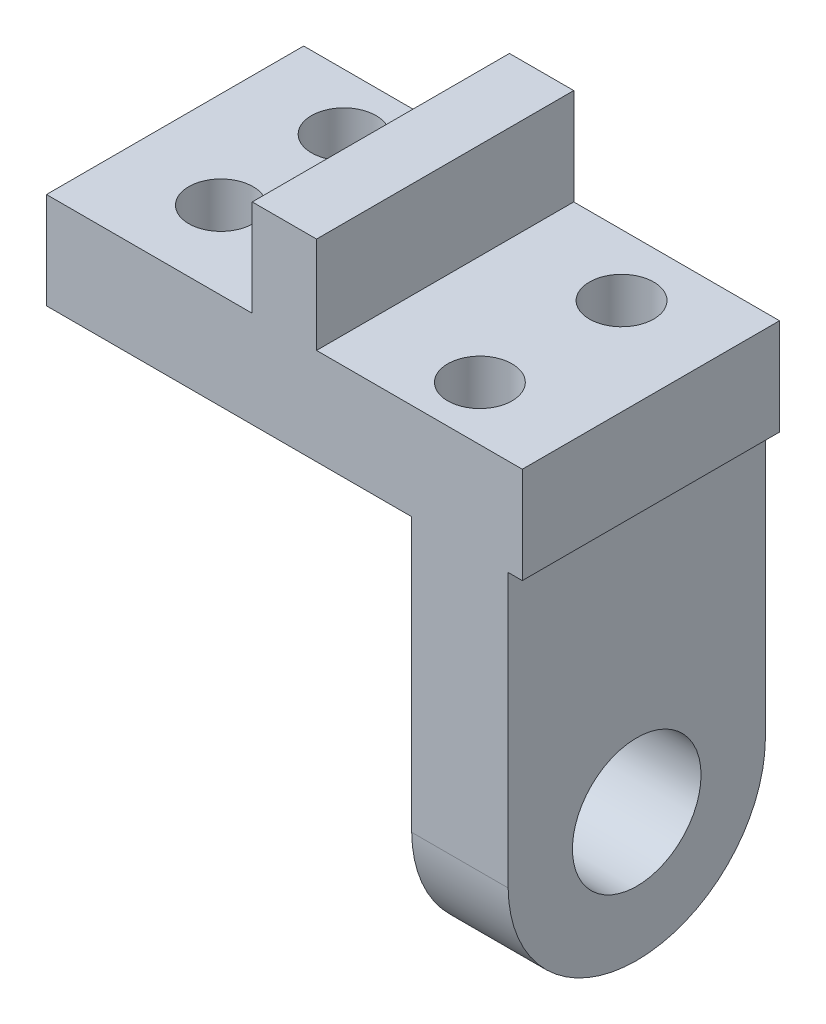
SolidWorks part; units mm, degrees
ref_plane "Front Plane" through (0, 0, 0) normal (0, 0, 1) x (1, 0, 0)
ref_plane "Top Plane" through (0, 0, 0) normal (0, 1, 0) x (1, 0, 0)
ref_plane "Right Plane" through (0, 0, 0) normal (1, 0, 0) x (0, 0, -1)
sketch "Sketch1" plane through (0, 0, 0) normal (0, 0, 1) x (1, 0, 0)
  line L1 (-56.7949, 15) -> (17.2051, 15)
  line L2 (-56.7949, 15) -> (-56.7949, 0)
  line L3 (-56.7949, 0) -> (17.2051, 0)
  line L4 (17.2051, 15) -> (17.2051, 0)
  dimension "D1" = 15
  dimension "D2" = 74
extrude "Boss-Extrude1" add sketch "Sketch1" along normal mid plane 40
sketch "Sketch2" plane through (0, 0, 0) normal (0, 1, 0) x (1, 0, 0)
  line L0 (-19.7949, 20) -> (-19.7949, -20) construction
  line L1 (17.2051, 20) -> (-56.7949, 20) construction
  line L2 (17.2051, -20) -> (-56.7949, -20) construction
  line L6 (-25.0987, -20) -> (-14.5497, -20)
  line L8 (-24.7949, 20) -> (-14.7949, 20)
  line L9 (-24.7949, 20) -> (-24.7949, -20)
  line L10 (-24.7949, -20) -> (-14.7949, -20)
  line L11 (-14.7949, 20) -> (-14.7949, -20)
  dimension "D1" = 10
  dimension "D2" = 5
extrude "Boss-Extrude2" add sketch "Sketch2" along normal blind 30 contours L9 L10 L11 L8
sketch "Sketch3" plane through (0, 0, 0) normal (0, 1, 0) x (1, 0, 0)
  line L0 (-56.7949, -20) -> (-56.7949, 20) construction
  circle A0 centre (-41.7949, 11.2385) radius 5.0247
  circle A1 centre (-41.7949, -5.5592) radius 5.0139
  point P6 (0, 0)
  point P7 (0, 0)
  dimension "D1" = 15
  dimension "D2" = 15
extrude "Cut-Extrude4" cut sketch "Sketch3" along normal up to surface (15 mm away) contours A0 up to face at (-40.7949, 15, 0)
sketch "Sketch6" plane through (0, 15, 0) normal (0, 1, 0) x (1, 0, 0)
  circle A0 centre (-41.7949, -7.8749) radius 5
extrude "Cut-Extrude5" cut sketch "Sketch6" against normal blind 30
sketch "Sketch8" plane through (0, 15, 0) normal (0, 1, 0) x (1, 0, 0)
  line L0 (17.2051, -20) -> (17.2051, 20) construction
  circle A0 centre (2.2051, 10.4357) radius 5
  dimension "D1" = 15
extrude "Cut-Extrude6" cut sketch "Sketch8" against normal blind 30
sketch "Sketch9" plane through (0, 15, 0) normal (0, 1, 0) x (1, 0, 0)
  line L0 (17.2051, -20) -> (17.2051, 20) construction
  circle A0 centre (2.2051, -11.5981) radius 5
  dimension "D1" = 15
extrude "Cut-Extrude7" cut sketch "Sketch9" against normal blind 30
sketch "Sketch11" plane through (0, 0, 0) normal (1, 0, 0) x (0, 0, -1)
  line L0 (-20, 7.5) -> (-20, -42.5)
  line L1 (-20, 7.5) -> (20, 7.5) construction
  line L4 (20, 7.5) -> (20, -42.5)
  arc A0 (-20, -42.5) -> (20, -42.5) centre (0, -42.2689) ccw
  circle A1 centre (0, -42.2689) radius 10
extrude "Boss-Extrude3" add sketch "Sketch11" along normal blind 15 contours L1 L0 A0 L4 A1
